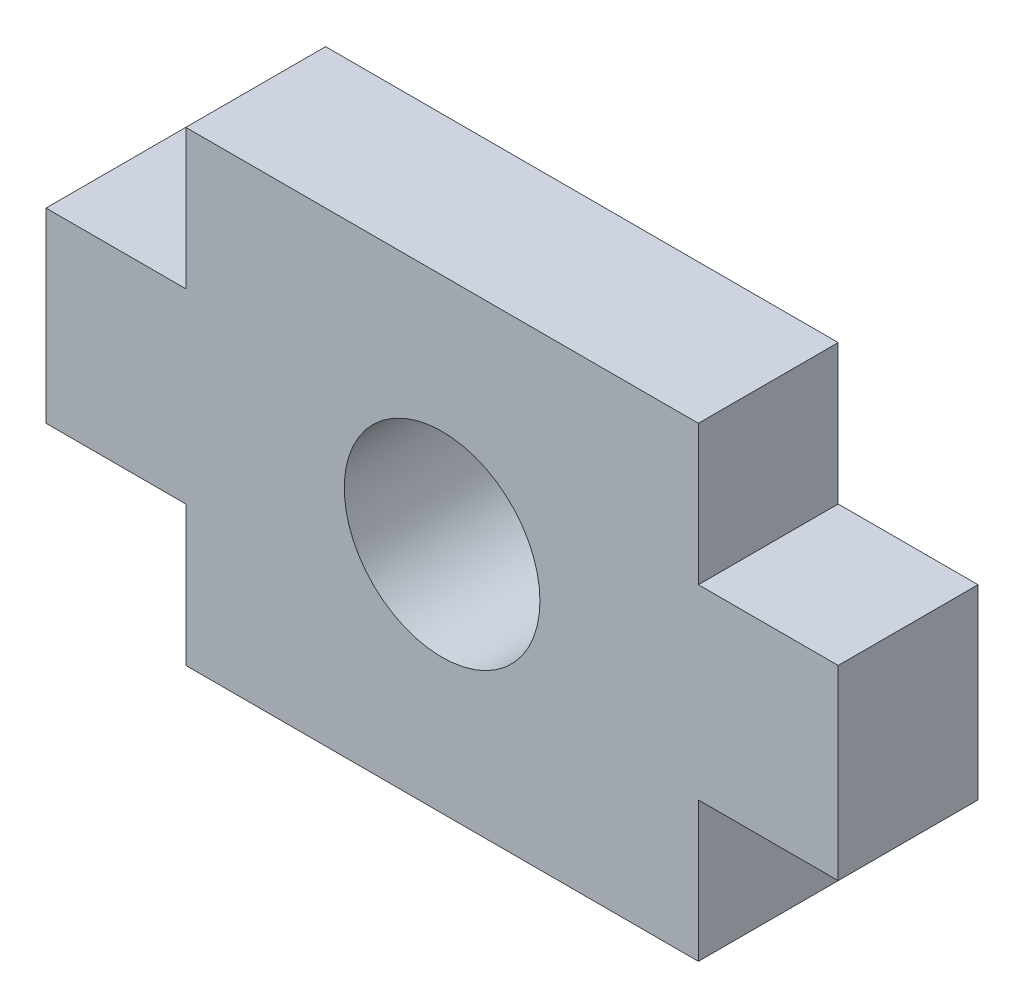
SolidWorks part; units mm, degrees
ref_plane "Plano frontal" through (0, 0, 0) normal (0, 0, 1) x (1, 0, 0)
ref_plane "Plano superior" through (0, 0, 0) normal (0, 1, 0) x (1, 0, 0)
ref_plane "Plano direito" through (0, 0, 0) normal (1, 0, 0) x (0, 0, -1)
sketch "Sketch1" plane through (0, 0, 0) normal (0, 0, 1) x (1, 0, 0)
  line L1 (-5.5, 5) -> (5.5, 5)
  line L2 (-5.5, 5) -> (-5.5, -5)
  line L3 (-5.5, -5) -> (5.5, -5)
  line L4 (5.5, 5) -> (5.5, -5)
  point P4 (4.8939, -3.1541)
  point P5 (0, 5)
  point P8 (-5.5, 0)
  dimension "D1" = 11
  dimension "D2" = 10
extrude "Boss-Extrude1" add sketch "Sketch1" along normal mid plane 3
sketch "Sketch3" plane through (0, 0, 0) normal (0, 0, 1) x (1, 0, 0)
  line L0 (-5.5, 5) -> (-5.5, -5) construction
  line L1 (-8.5, 2) -> (-5.5, 2)
  line L2 (-8.5, 2) -> (-8.5, -2)
  line L3 (-8.5, -2) -> (-5.5, -2)
  line L4 (-5.5, 2) -> (-5.5, -2)
  line L5 (-5.5, -5) -> (5.5, -5) construction
  line L6 (5.5, 5) -> (-5.5, 5) construction
  line L7 (0, -1.65) -> (0, 1.65) construction
  line L8 (5.5, 2) -> (5.5, -2)
  line L9 (8.5, -2) -> (5.5, -2)
  line L10 (8.5, 2) -> (8.5, -2)
  line L11 (8.5, 2) -> (5.5, 2)
  dimension "D1" = 3
  dimension "D2" = 3
  dimension "D3" = 3
extrude "Boss-Extrude2" add sketch "Sketch3" along normal mid plane 3
sketch "Sketch4" plane through (0, 0, 0) normal (0, 0, 1) x (1, 0, 0)
  circle A0 centre (0, 0) radius 2 construction
  circle A1 centre (0, 0) radius 2.1
  dimension "D1" = 4
  dimension "D2" = 0.1
extrude "Cut-Extrude1" cut sketch "Sketch4" against normal through all both and the other way through all
